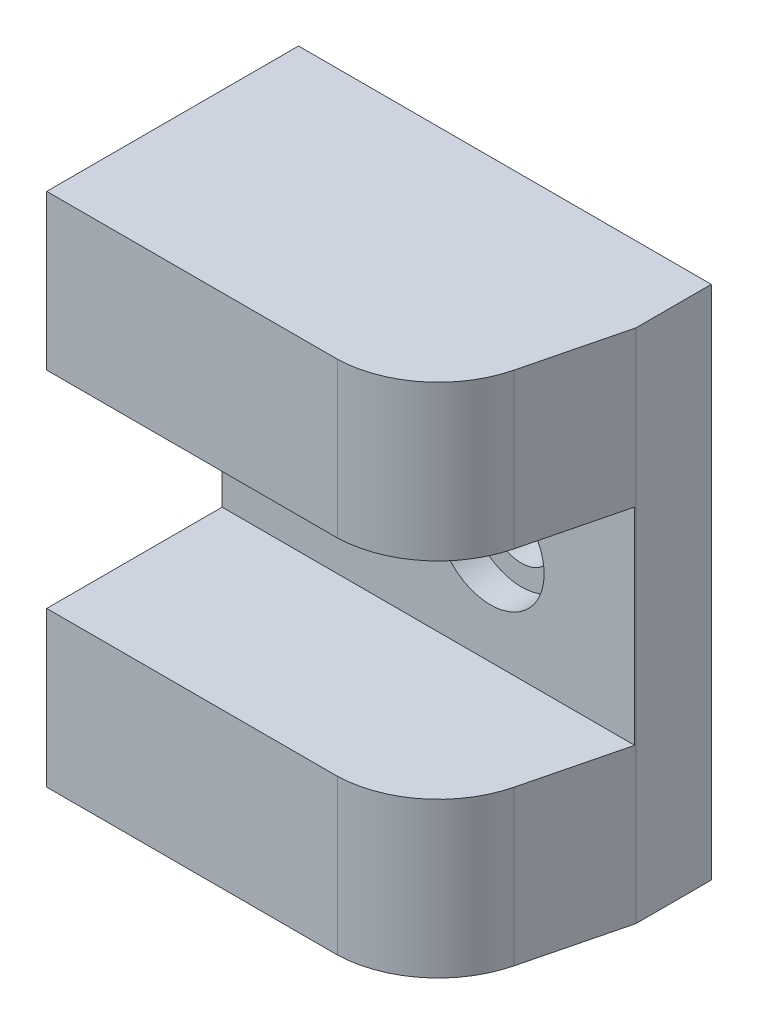
SolidWorks part; units mm, degrees
ref_plane "前视基准面" through (0, 0, 0) normal (0, 0, 1) x (1, 0, 0)
ref_plane "上视基准面" through (0, 0, 0) normal (0, 1, 0) x (1, 0, 0)
ref_plane "右视基准面" through (0, 0, 0) normal (1, 0, 0) x (0, 0, -1)
sketch "草图1" plane through (0, 0, 0) normal (0, 0, 1) x (1, 0, 0)
  line L0 (130, 105) -> (130, -105) construction
  line L1 (130, 80) -> (110, 80)
  line L2 (130, 80) -> (130, 105)
  line L4 (110, 80) -> (110, 105)
  line L5 (75, 105) -> (130, 105) construction
  line L6 (130, 105) -> (110, 105)
  dimension "D1" = 20
  dimension "D2" = 25
extrude "凸台-拉伸1" add sketch "草图1" along normal blind 12.2
sketch "草图2" plane through (0, 105, 0) normal (0, 1, 0) x (1, 0, 0)
  line L0 (130, -12.2) -> (130, 0) construction
  line L6 (128.82, -8.3843) -> (130, -3.6517)
  line L8 (130, -3.6517) -> (130, -12.2)
  line L10 (130, -12.2) -> (124.083, -12.2)
  line L11 (130, -12.2) -> (110, -12.2) construction
  arc A1 (124.083, -12.2) -> (128.82, -8.3843) centre (123.9333, -7.1659) ccw
  dimension "D1" = 5.917
extrude "切除-拉伸1" cut sketch "草图2" against normal blind 26.5
sketch "草图3" plane through (0, 0, 12.2) normal (0, 0, 1) x (1, 0, 0)
  line L0 (110, 92.5) -> (130, 92.5) construction
  line L1 (110, 105) -> (110, 80) construction
  line L4 (110, 97.5) -> (130, 97.5)
  line L5 (110, 97.5) -> (110, 87.5)
  line L6 (110, 87.5) -> (130, 87.5)
  line L7 (130, 97.5) -> (130, 87.5)
  line L8 (110, 97.5) -> (130, 87.5) construction
  line L9 (110, 87.5) -> (130, 97.5) construction
  point P6 (120, 92.5)
  dimension "D1" = 10
  dimension "D2" = 20
extrude "切除-拉伸2" cut sketch "草图3" against normal blind 8.5
sketch "草图4" plane through (0, 0, 3.7) normal (0, 0, 1) x (1, 0, 0)
  line L0 (110, 92.5) -> (129.988, 92.5) construction
  line L1 (110, 97.5) -> (110, 87.5) construction
  line L2 (129.988, 87.5) -> (129.988, 97.5) construction
  circle A0 centre (115, 92.5) radius 1.5
  circle A2 centre (123, 92.5) radius 1.5
  dimension "D1" = 3
  dimension "D2" = 8
  dimension "D3" = 5
hole_wizard "M3 六角头螺栓的柱形沉头孔1" positions "草图7" profile "草图8" counterbore size "M3" standard "GB" end condition through all
sketch "草图7" plane through (0, 0, 3.7) normal (0, 0, 1) x (1, 0, 0)
  point P0 (115, 92.5)
  point P3 (123, 92.5)
sketch "草图8" plane through (115, 92.5, 3.7) normal (1, 0, 0) x (0, -1, 0)
  line L0 (0, 0) -> (0, 3.7)
  line L1 (0, 3.7) -> (1.6, 3.7)
  line L3 (1.6, 3.7) -> (1.6, 1.5)
  line L4 (1.6, 1.5) -> (2.6, 1.5)
  line L5 (2.6, 1.5) -> (2.6, 0)
  line L7 (2.6, 0) -> (0, 0)
  line L11 (0, -6.35) -> (0, 107.95) construction
  dimension "通孔孔直径" = 3.2
  dimension "通孔孔深度" = 3.7
  dimension "柱形沉头孔直径" = 5.2
  dimension "柱形沉头孔深度" = 1.5
move or copy body "实体-移动/复制1" [suppressed] bodies to move or copy 109
